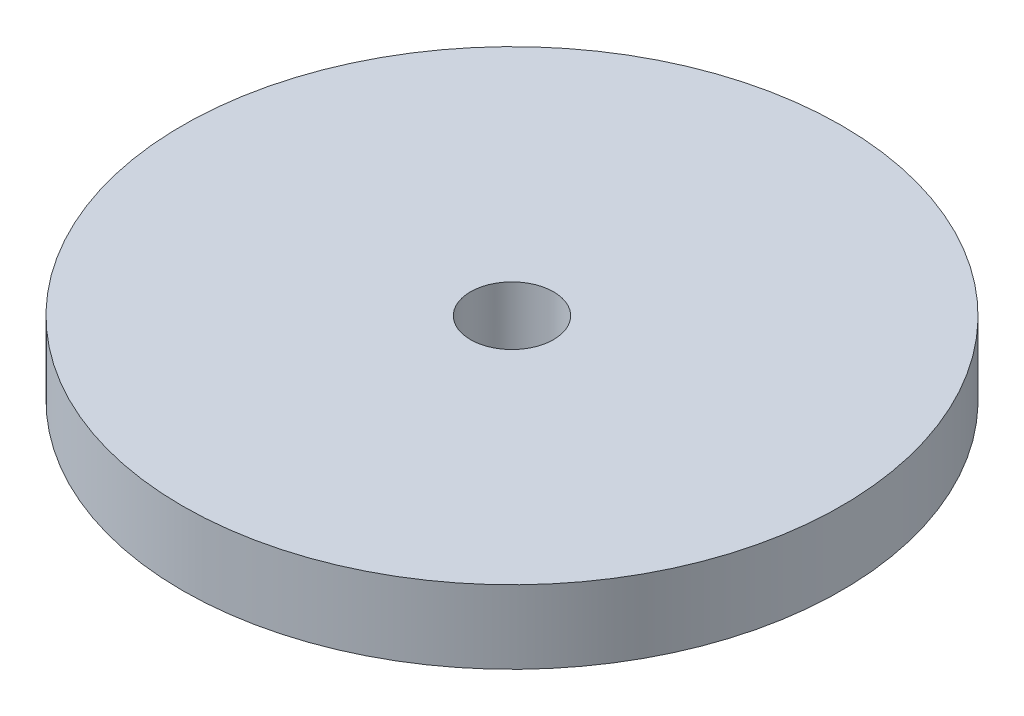
SolidWorks part; units mm, degrees
ref_plane "Front Plane" through (0, 0, 0) normal (0, 0, 1) x (1, 0, 0)
ref_plane "Top Plane" through (0, 0, 0) normal (0, 1, 0) x (1, 0, 0)
ref_plane "Right Plane" through (0, 0, 0) normal (1, 0, 0) x (0, 0, -1)
sketch "Sketch1" plane through (0, 0, 0) normal (0, 1, 0) x (1, 0, 0)
  circle A0 centre (0, 0) radius 13.5
  dimension "D1" = 27
extrude "Boss-Extrude1" add sketch "Sketch1" along normal blind 3
sketch "Sketch5" plane through (0, 0, 0) normal (0, -1, 0) x (-1, 0, 0)
  point P0 (0, 0)
hole_wizard "M3 Clearance Hole1" positions "Sketch5" profile "Sketch4" hole size "M3" standard "ISO" end condition up to next
sketch "Sketch4" plane through (0, 0, 0) normal (1, 0, 0) x (0, 0, -1)
  line L0 (0, 0) -> (0, 3)
  line L1 (0, 3) -> (1.7, 3)
  line L2 (1.7, 3) -> (1.7, 0.025)
  line L3 (1.7, 0.025) -> (1.725, 0)
  line L5 (1.725, 0) -> (0, 0)
  line L6 (-1.7, 0.025) -> (-1.725, 0) construction
  line L11 (0, -6.35) -> (0, 107.95) construction
  dimension "Thru Hole Dia." = 3.4
  dimension "Thru Hole Depth" = 3
  dimension "Near C'Sink Dia." = 3.45
  dimension "Near C'Sink Angle" = 90
